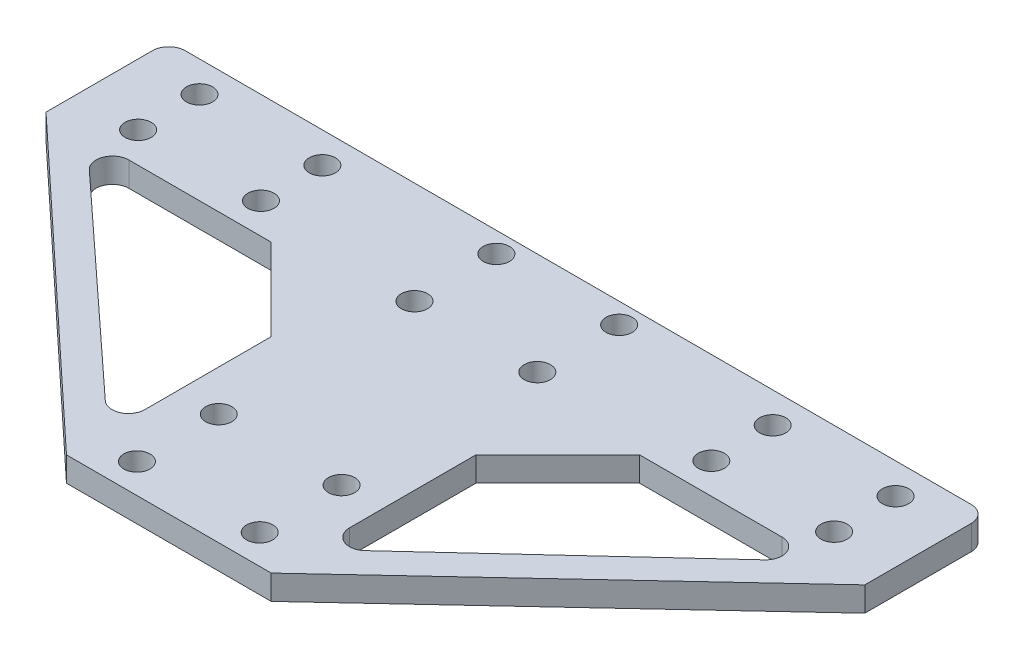
SolidWorks part; units mm, degrees
ref_plane "前视基准面" through (0, 0, 0) normal (0, 0, 1) x (1, 0, 0)
ref_plane "上视基准面" through (0, 0, 0) normal (0, 1, 0) x (1, 0, 0)
ref_plane "右视基准面" through (0, 0, 0) normal (1, 0, 0) x (0, 0, -1)
other "Configuration Table"
sketch "草图1" plane through (0, 0, 0) normal (0, 1, 0) x (1, 0, 0)
  line L1 (-50, -7.5) -> (50, -7.5)
  line L2 (-50, -7.5) -> (-50, 7.5)
  line L3 (-50, 7.5) -> (50, 7.5)
  line L4 (50, -7.5) -> (50, 7.5)
  line L5 (-50, -7.5) -> (50, 7.5) construction
  line L6 (-50, 7.5) -> (50, -7.5) construction
  point P0 (0, 0)
  dimension "D1" = 100
  dimension "D2" = 15
extrude "凸台-拉伸1" add sketch "草图1" along normal blind 3
sketch "草图2" plane through (0, 3, 0) normal (0, 1, 0) x (1, 0, 0)
  line L0 (50, 7.5) -> (-50, 7.5) construction
  line L1 (-12.5, 7.5) -> (12.5, 7.5)
  line L2 (-12.5, 7.5) -> (-12.5, -42.5)
  line L3 (-12.5, -42.5) -> (12.5, -42.5)
  line L4 (12.5, 7.5) -> (12.5, -42.5)
  line L5 (0, 0) -> (0, -13.2749) construction
  dimension "D1" = 25
  dimension "D2" = 50
extrude "凸台-拉伸2" add sketch "草图2" against normal blind 3
sketch "草图3" plane through (0, 3, 0) normal (0, 1, 0) x (1, 0, 0)
  line L0 (0, 7.5) -> (0, -8.6676) construction
  line L1 (50, 7.5) -> (-50, 7.5) construction
  line L2 (-50, 0) -> (0, 0) construction
  line L3 (-50, 7.5) -> (-50, -7.5) construction
  line L4 (-35, 7.5) -> (-35, -7.5) construction
  line L5 (-50, -7.5) -> (-12.5, -7.5) construction
  circle A0 centre (-42.5, 3.75) radius 1.6
  circle A1 centre (-42.5, -3.75) radius 1.6
  circle A2 centre (-27.5, -3.75) radius 1.6
  circle A3 centre (-27.5, 3.75) radius 1.6
  circle A4 centre (27.5, -3.75) radius 1.6
  circle A5 centre (42.5, -3.75) radius 1.6
  circle A6 centre (42.5, 3.75) radius 1.6
  circle A7 centre (27.5, 3.75) radius 1.6
  circle A8 centre (-7.5, 5) radius 1.6
  circle A9 centre (-7.5, -5) radius 1.6
  circle A10 centre (7.5, -5) radius 1.6
  circle A11 centre (7.5, 5) radius 1.6
  circle A12 centre (-7.5, -28.9) radius 1.6
  circle A13 centre (-7.5, -38.9) radius 1.6
  circle A14 centre (7.5, -38.9) radius 1.6
  circle A15 centre (7.5, -28.9) radius 1.6
  dimension "D2" = 3.2
  dimension "D5" = 3.2
  dimension "D1" = 35
  dimension "D3" = 7.5
  dimension "D4" = 3.75
  dimension "D6" = 15
  dimension "D7" = 10
  dimension "D8" = 2
extrude "切除-拉伸1" cut sketch "草图3" against normal blind 3
sketch "草图4" plane through (0, 3, 0) normal (0, 1, 0) x (1, 0, 0)
  line L0 (-50, -7.5) -> (-12.5, -42.5)
  line L1 (-12.5, -42.5) -> (-12.5, -37.5)
  line L2 (-12.5, -7.5) -> (-12.5, -42.5) construction
  line L3 (-12.5, -37.5) -> (-45, -7.5)
  line L4 (-50, -7.5) -> (-12.5, -7.5) construction
  line L5 (-45, -7.5) -> (-50, -7.5)
  line L6 (0, 0) -> (0, -9.3553) construction
  line L7 (12.5, -37.5) -> (45, -7.5)
  line L8 (12.5, -42.5) -> (12.5, -37.5)
  line L9 (50, -7.5) -> (12.5, -42.5)
  line L10 (45, -7.5) -> (50, -7.5)
  dimension "D1" = 5
  dimension "D2" = 5
extrude "凸台-拉伸3" add sketch "草图4" against normal blind 3
chamfer "倒角1" distance 10 angle 45 2 edges at (12.5, 1.5, 7.5) (-12.5, 1.5, 7.5)
fillet "圆角2" radius 2 6 edges at (50, 1.5, -7.5) (-50, 1.5, -7.5) (45, 1.5, 7.5) (12.5, 1.5, 37.5) (-12.5, 1.5, 37.5) (-45, 1.5, 7.5)
